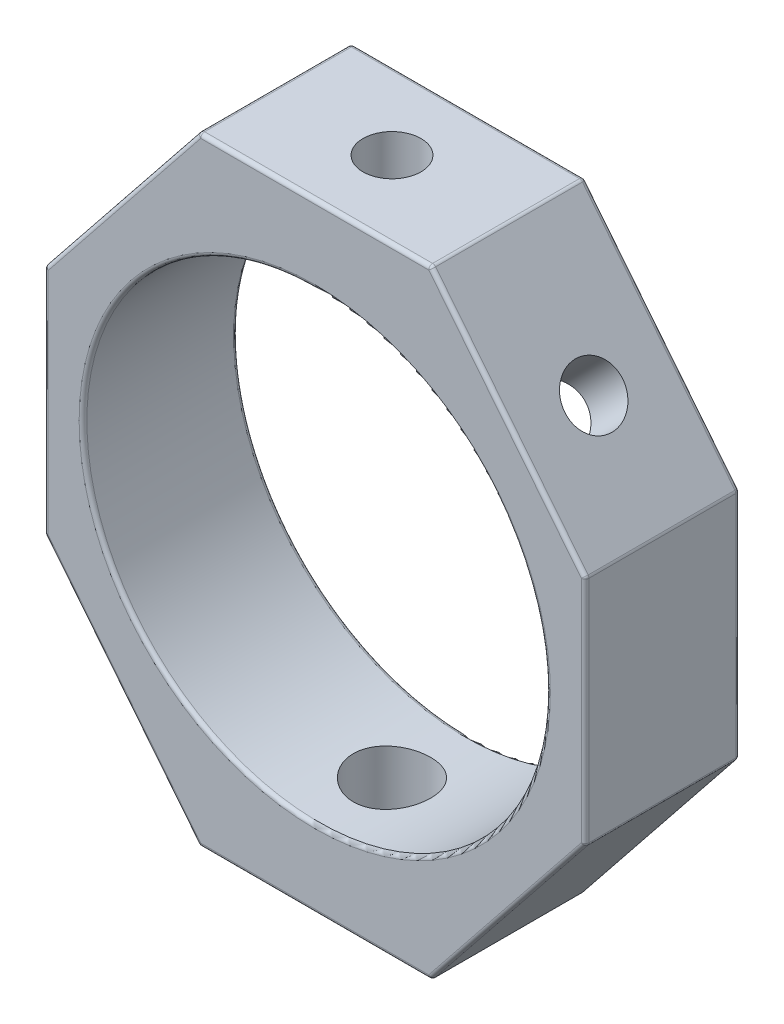
SolidWorks part; units mm, degrees
ref_plane "Front Plane" through (0, 0, 0) normal (0, 0, 1) x (1, 0, 0)
ref_plane "Top Plane" through (0, 0, 0) normal (0, 1, 0) x (1, 0, 0)
ref_plane "Right Plane" through (0, 0, 0) normal (1, 0, 0) x (0, 0, -1)
sketch "Sketch1" plane through (0, 0, 0) normal (0, 0, 1) x (1, 0, 0)
  line L0 (-37.6956, 0) -> (37.6956, 0) construction
  line L1 (-14, 6) -> (-14, -6)
  line L2 (0, -55) -> (0, 55) construction
  line L3 (14, 6) -> (14, -6)
  line L4 (-6, 16) -> (-14, 6)
  line L5 (0, 31.48) -> (0, -31.48) construction
  line L6 (-6, 16) -> (6, 16)
  line L7 (55, 0) -> (-55, 0) construction
  line L8 (-6, -16) -> (6, -16)
  line L9 (-14, -6) -> (-6, -16)
  line L10 (6, -16) -> (14, -6)
  line L11 (14, 6) -> (6, 16)
  circle A1 centre (0, 0) radius 12
  point P5 (0, 0)
  point P9 (-14, 0)
  point P10 (-14, 0)
  point P14 (0, 0)
  point P20 (0, 16)
  dimension "D1" = 24
  dimension "D3" = 16
  dimension "D2" = 14
extrude "Boss-Extrude1" add sketch "Sketch1" along normal mid plane 8
sketch "Sketch2" plane through (0, 0, 0) normal (0, 0, 1) x (1, 0, 0)
  line L1 (7.5905, 7.5905) -> (12.8915, 12.8915)
  line L2 (12.8915, 12.8915) -> (11.8308, 13.9521)
  line L3 (11.8308, 13.9521) -> (6.5298, 8.6512)
  line L4 (6.5298, 8.6512) -> (7.5905, 7.5905)
  point P5 (0, 0)
revolve "Cut-Revolve1" cut sketch "Sketch2" angle 360 about L1
sketch "Sketch3" plane through (0, 16, 0) normal (0, 1, 0) x (1, 0, 0)
  circle A0 centre (0, 0) radius 1.5
  dimension "D1" = 3
extrude "Cut-Extrude1" cut sketch "Sketch3" against normal blind 8
sketch "Sketch4" plane through (0, -16, 0) normal (0, -1, 0) x (1, 0, 0)
  circle A0 centre (0, 0) radius 2
  dimension "D1" = 4
extrude "Cut-Extrude2" cut sketch "Sketch4" against normal blind 8
fillet "Fillet1" radius 0.2 26 edges at (12, 0, -4) (12, 0, 4) (-10, -11, -4) (0, -16, -4) (10, -11, -4) (14, 0, -4) (10, 11, -4) (0, 16, -4) (-10, 11, -4) (-14, 0, -4) (-10, -11, 4) (0, -16, 4) (10, -11, 4) (14, 0, 4) (0, 16, 4) (-10, 11, 4) (-14, 0, 4) (-14, -6, 0) (-14, 6, 0) (-6, 16, 0) (6, 16, 0) (14, 6, 0) (14, -6, 0) (6, -16, 0) (-6, -16, 0) (10, 11, 4)
